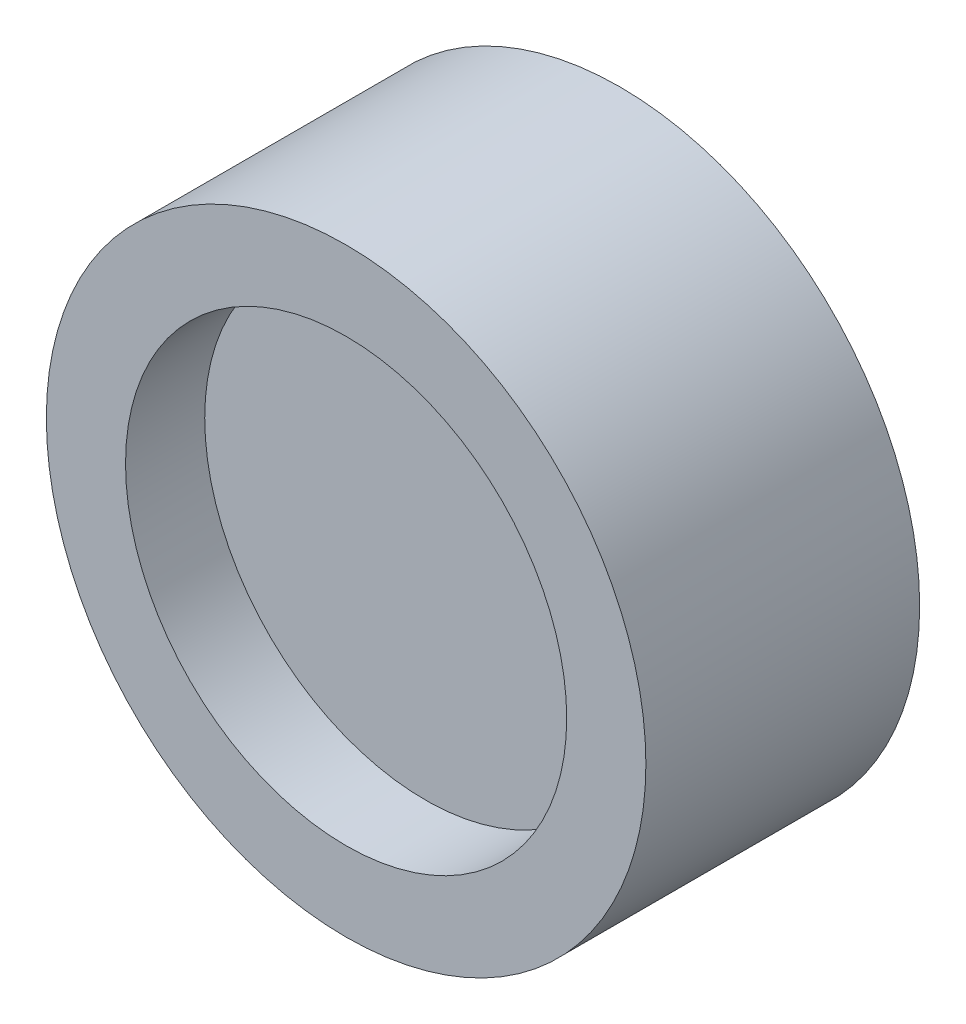
SolidWorks part; units mm, degrees
ref_plane "正面" through (0, 0, 0) normal (0, 0, 1) x (1, 0, 0)
ref_plane "平面" through (0, 0, 0) normal (0, 1, 0) x (1, 0, 0)
ref_plane "右側面" through (0, 0, 0) normal (1, 0, 0) x (0, 0, -1)
sketch "ｽｹｯﾁ1" plane through (0, 0, 0) normal (0, 0, 1) x (1, 0, 0)
  circle A0 centre (0, 0) radius 26.5
  circle A1 centre (0, 0) radius 19.5
extrude "ﾎﾞｽ - 押し出し1" add sketch "ｽｹｯﾁ1" along normal blind 24.2
sketch "ｽｹｯﾁ2" plane through (0, 0, 0) normal (0, 0, -1) x (-1, 0, 0)
  circle A0 centre (0, 0) radius 19.5
extrude "ﾎﾞｽ - 押し出し7" add sketch "ｽｹｯﾁ2" against normal blind 10.2 from offset 7 offset against normal yes
sketch "ｽｹｯﾁ4" plane through (0, 0, 0) normal (0, 0, -1) x (-1, 0, 0)
  circle A0 centre (0, 0) radius 3
extrude "ﾎﾞｽ - 押し出し8" add sketch "ｽｹｯﾁ4" along normal blind 3 from offset 7 separate body
